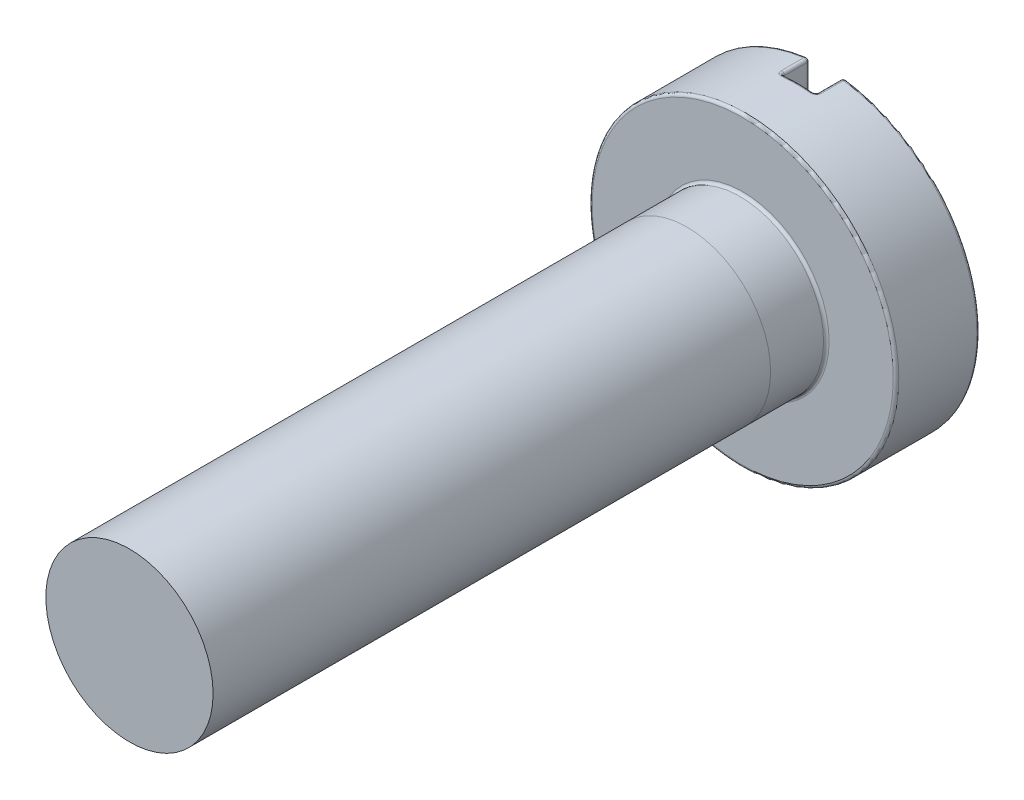
SolidWorks part; units mm, degrees
ref_plane "Front Plane" through (0, 0, 0) normal (0, 0, 1) x (1, 0, 0)
ref_plane "Top Plane" through (0, 0, 0) normal (0, 1, 0) x (1, 0, 0)
ref_plane "Right Plane" through (0, 0, 0) normal (1, 0, 0) x (0, 0, -1)
sketch "Sketch1" plane through (0, 0, 0) normal (0, 0, 1) x (1, 0, 0)
  circle A0 centre (0, 0) radius 1.5
  dimension "D1" = 3
extrude "Boss-Extrude1" add sketch "Sketch1" along normal blind 11
sketch "Sketch2" plane through (0, 0, 0) normal (0, 0, 1) x (1, 0, 0)
  circle A2 centre (0, 0) radius 2.75
  circle A3 centre (0, 0) radius 2.75
  dimension "D1" = 1.25
extrude "Boss-Extrude2" add sketch "Sketch2" against normal blind 1.5
sketch "Sketch3" plane through (0, 0, -1.5) normal (0, 0, -1) x (-1, 0, 0)
  line L1 (0.3, -6.7813) -> (-0.3, -6.7813)
  line L2 (0.3, -6.7813) -> (0.3, 6.7813)
  line L3 (0.3, 6.7813) -> (-0.3, 6.7813)
  line L4 (-0.3, -6.7813) -> (-0.3, 6.7813)
  line L5 (0.3, -6.7813) -> (-0.3, 6.7813) construction
  line L6 (0.3, 6.7813) -> (-0.3, -6.7813) construction
  point P0 (0, 0)
  dimension "D1" = 0.6
extrude "Cut-Extrude1" cut sketch "Sketch3" against normal blind 0.5
fillet "Fillet1" radius 0.05 12 edges at (-0.3, -2.7336, -1.25) (-0.3, 2.7336, -1.25) (0.3, 2.7336, -1.25) (0.3, -2.7336, -1.25) (0, 2.75, -1) (0, -2.75, -1) (0.3, 0, -1) (-0.3, 0, -1) (-0.3, 0, -1.5) (-2.75, 0, -1.5) (0.3, 0, -1.5) (2.75, 0, -1.5)
fillet "Fillet2" radius 0.05 2 edges at (2.75, 0, 0) (1.5, 0, 0)
sketch "Sketch4" plane through (0, 0, 0) normal (1, 0, 0) x (0, 0, -1)
  line L0 (-1, -3.6683) -> (-1, 4.4314)
  line L1 (-11, 1.5) -> (-11, -1.5) construction
  dimension "D1" = 10
split line "Split Line1"
